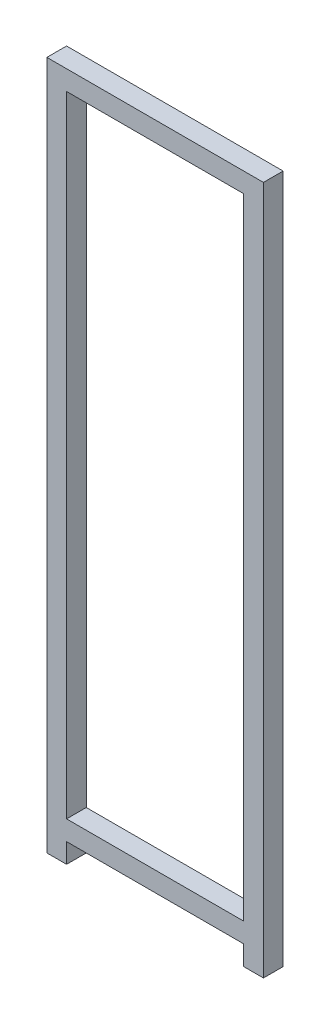
SolidWorks part; units mm, degrees
ref_plane "Alzado" through (0, 0, 0) normal (0, 0, 1) x (1, 0, 0)
ref_plane "Planta" through (0, 0, 0) normal (0, 1, 0) x (1, 0, 0)
ref_plane "Vista lateral" through (0, 0, 0) normal (1, 0, 0) x (0, 0, -1)
sketch "Croquis1" plane through (0, 0, 0) normal (0, 0, 1) x (1, 0, 0)
  line L0 (-275, -1500) -> (-275, 250)
  line L1 (-275, 250) -> (275, 250)
  line L2 (275, 250) -> (275, -1500)
  line L3 (275, -1500) -> (225, -1500)
  line L4 (225, -1500) -> (225, -1450)
  line L5 (225, 200) -> (-225, 200)
  line L6 (-225, 200) -> (-225, -1400)
  line L7 (-225, -1500) -> (-275, -1500)
  line L8 (225, -1400) -> (-225, -1400)
  line L9 (-225, -1450) -> (-225, -1500)
  line L10 (-225, -1450) -> (225, -1450)
  line L11 (225, -1400) -> (225, 200)
  point P3 (-225, -1256.8345)
  point P9 (0, 200)
  dimension "D1" = 550
  dimension "D2" = 1750
  dimension "D3" = 50
  dimension "D4" = 50
  dimension "D5" = 50
  dimension "D6" = 200
  dimension "D7" = 50
  dimension "D8" = 50
extrude "Saliente-Extruir1" add sketch "Croquis1" against normal blind 50
